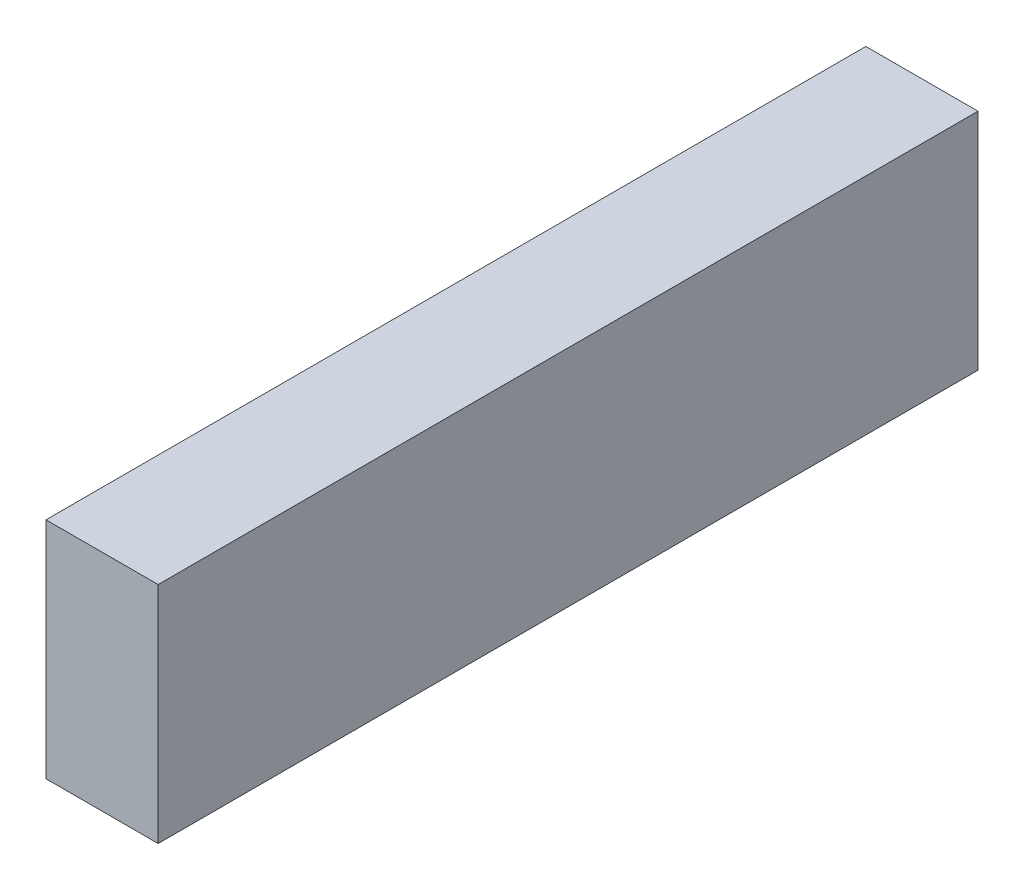
SolidWorks part; units mm, degrees
ref_plane "Front Plane" through (0, 0, 0) normal (0, 0, 1) x (1, 0, 0)
ref_plane "Top Plane" through (0, 0, 0) normal (0, 1, 0) x (1, 0, 0)
ref_plane "Right Plane" through (0, 0, 0) normal (1, 0, 0) x (0, 0, -1)
sketch "Sketch1" plane through (0, 0, 0) normal (1, 0, 0) x (0, 0, -1)
  line L1 (0, 0) -> (73.1, 0)
  line L2 (0, 0) -> (0, 20)
  line L3 (0, 20) -> (73.1, 20)
  line L4 (73.1, 0) -> (73.1, 20)
extrude "Boss-Extrude1" add sketch "Sketch1" against normal blind 10
